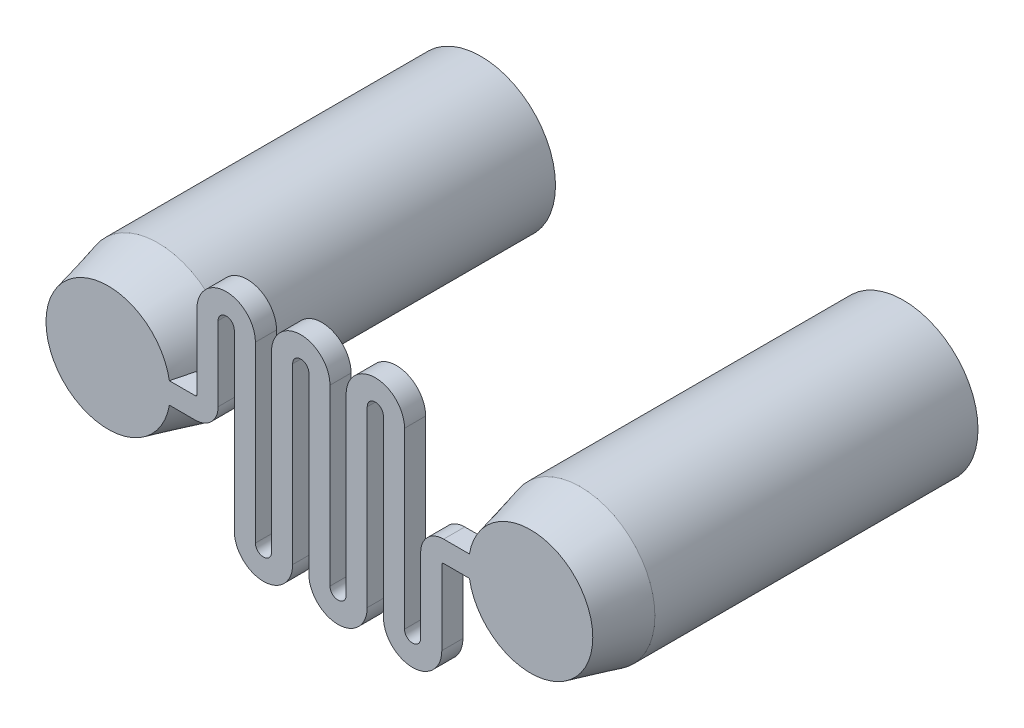
SolidWorks part; units mm, degrees
ref_plane "Front Plane" through (0, 0, 0) normal (0, 0, 1) x (1, 0, 0)
ref_plane "Top Plane" through (0, 0, 0) normal (0, 1, 0) x (1, 0, 0)
ref_plane "Right Plane" through (0, 0, 0) normal (1, 0, 0) x (0, 0, -1)
sketch "Sketch2" plane through (0, 0, 0) normal (0, 0, 1) x (1, 0, 0)
  line L3 (-20.5, -0.85) -> (-13.5, -0.85)
  line L6 (-11.65, 1) -> (-11.65, 7)
  line L9 (-10.35, 7) -> (-10.35, 0)
  line L12 (-10.35, 0) -> (-10.35, -7)
  line L15 (-5.65, -7) -> (-5.65, 0)
  line L18 (-5.65, 0) -> (-5.65, 7)
  line L21 (-4.35, 7) -> (-4.35, 0)
  line L22 (-4.35, 0) -> (-4.35, -7)
  line L23 (0.35, -7) -> (0.35, 0)
  line L24 (0.35, 0) -> (0.35, 7)
  line L25 (1.65, 7) -> (1.65, 0)
  line L26 (1.65, 0) -> (1.65, -7)
  line L27 (6.35, -7) -> (6.35, -1)
  line L28 (6.5, -0.85) -> (13.5, -0.85)
  line L29 (-20.5, 0.85) -> (-13.5, 0.85)
  line L30 (-13.35, 1) -> (-13.35, 7)
  line L31 (-8.65, 7) -> (-8.65, 0)
  line L32 (-8.65, 0) -> (-8.65, -7)
  line L33 (-7.35, -7) -> (-7.35, 0)
  line L34 (-7.35, 0) -> (-7.35, 7)
  line L35 (-2.65, 7) -> (-2.65, 0)
  line L36 (-2.65, 0) -> (-2.65, -7)
  line L37 (-1.35, -7) -> (-1.35, 0)
  line L38 (-1.35, 0) -> (-1.35, 7)
  line L39 (3.35, 7) -> (3.35, 0)
  line L40 (3.35, 0) -> (3.35, -7)
  line L41 (4.65, -7) -> (4.65, -1)
  line L42 (6.5, 0.85) -> (13.5, 0.85)
  arc A8 (-11.65, 1) -> (-13.5, -0.85) centre (-13.5, 1) cw
  arc A9 (-11.65, 7) -> (-10.35, 7) centre (-11, 7) cw
  arc A10 (-10.35, -7) -> (-5.65, -7) centre (-8, -7) ccw
  arc A11 (-5.65, 7) -> (-4.35, 7) centre (-5, 7) cw
  arc A12 (-4.35, -7) -> (0.35, -7) centre (-2, -7) ccw
  arc A13 (0.35, 7) -> (1.65, 7) centre (1, 7) cw
  arc A14 (1.65, -7) -> (6.35, -7) centre (4, -7) ccw
  arc A15 (6.35, -1) -> (6.5, -0.85) centre (6.5, -1) cw
  arc A16 (-13.35, 1) -> (-13.5, 0.85) centre (-13.5, 1) cw
  arc A17 (-13.35, 7) -> (-8.65, 7) centre (-11, 7) cw
  arc A18 (-8.65, -7) -> (-7.35, -7) centre (-8, -7) ccw
  arc A19 (-7.35, 7) -> (-2.65, 7) centre (-5, 7) cw
  arc A20 (-2.65, -7) -> (-1.35, -7) centre (-2, -7) ccw
  arc A21 (-1.35, 7) -> (3.35, 7) centre (1, 7) cw
  arc A22 (3.35, -7) -> (4.65, -7) centre (4, -7) ccw
  arc A23 (4.65, -1) -> (6.5, 0.85) centre (6.5, -1) cw
  arc A24 (-20.5, 0.85) -> (-20.5, -0.85) centre (-20.5, 0) ccw
  arc A25 (13.5, -0.85) -> (13.5, 0.85) centre (13.5, 0) ccw
  point P4 (0, 0)
  point P32 (5.5, 0)
  point P35 (-12.5, 0)
  dimension "D14" = 8
extrude "Boss-Extrude1" add sketch "Sketch2" along normal blind 1.7
ref_plane "Plane1" through (0, 0, 0) normal (0, 1, 0) x (1, 0, 0)
ref_plane "Plane2" through (0, 0, 0) normal (0, 1, 0) x (1, 0, 0)
sketch "Sketch3" plane through (0, 0, 0) normal (0, 1, 0) x (1, 0, 0)
  line L0 (-20.5, -1.7) -> (-25.5, -1.7)
  line L2 (-20.5, -1.7) -> (-20.5, 28.3)
  line L3 (-20.5, 28.3) -> (-26.5, 28.3)
  line L4 (-26.5, 28.3) -> (-26.5, 2.3)
  line L5 (-26.5, 2.3) -> (-25.5, -1.7)
  dimension "D1" = 5
  dimension "D3" = 30
  dimension "D4" = 6
revolve "Revolve1" add sketch "Sketch3" angle 360 about L2
sketch "Sketch4" plane through (0, 0, 0) normal (0, 1, 0) x (1, 0, 0)
  line L0 (13.5, -1.7) -> (18.5, -1.7)
  line L2 (13.5, -1.7) -> (13.5, 28.3)
  line L3 (13.5, 28.3) -> (19.5, 28.3)
  line L4 (19.5, 28.3) -> (19.5, 2.3)
  line L5 (19.5, 2.3) -> (18.5, -1.7)
  dimension "D1" = 5
  dimension "D3" = 6
  dimension "D4" = 30
revolve "Revolve2" add sketch "Sketch4" angle 360 about L2
sketch "Sketch5" plane through (0, 0, -28.3) normal (0, 0, -1) x (-1, 0, 0)
  circle A0 centre (-13.5, 0) radius 5
  circle A1 centre (20.5, 0) radius 5
  dimension "D1" = 10
  dimension "D2" = 10
extrude "Cut-Extrude1" cut sketch "Sketch5" against normal blind 28
